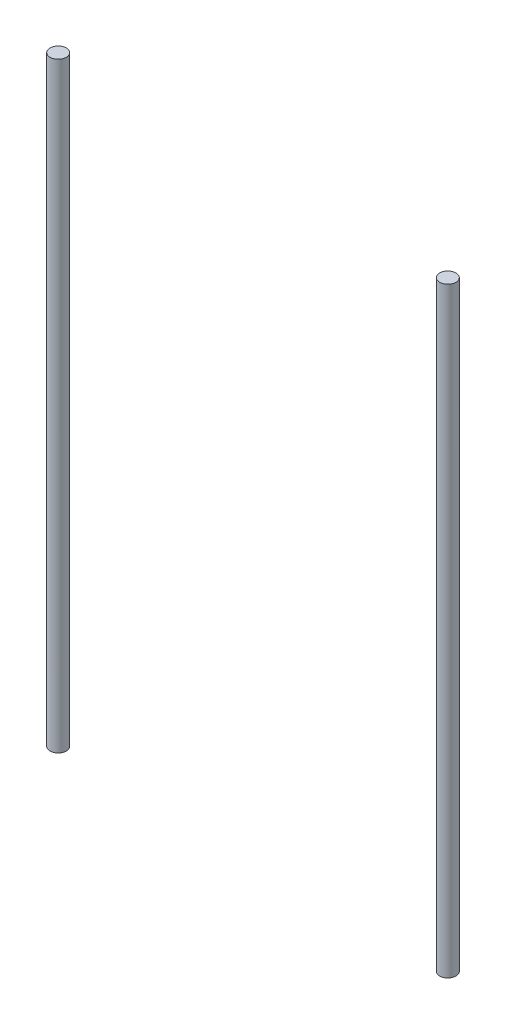
SolidWorks part; units mm, degrees
ref_plane "Front Plane" through (0, 0, 0) normal (0, 0, 1) x (1, 0, 0)
ref_plane "Top Plane" through (0, 0, 0) normal (0, 1, 0) x (1, 0, 0)
ref_plane "Right Plane" through (0, 0, 0) normal (1, 0, 0) x (0, 0, -1)
sketch "Sketch1" plane through (0, 0, 0) normal (0, 0, 1) x (1, 0, 0)
  line L0 (0, 0) -> (0, 245) construction
  line L1 (-287.5, 470) -> (287.5, 470)
  line L2 (-287.5, 470) -> (-287.5, -470)
  line L3 (-287.5, -470) -> (287.5, -470)
  line L4 (287.5, 470) -> (287.5, -470)
  line L5 (-287.5, 470) -> (287.5, -470) construction
  line L6 (-287.5, -470) -> (287.5, 470) construction
  line L7 (240, 60) -> (-240, 60)
  line L8 (240, 60) -> (240, 430)
  line L9 (240, 430) -> (-240, 430)
  line L10 (-240, 60) -> (-240, 430)
  line L11 (240, 60) -> (-240, 430) construction
  line L12 (240, 430) -> (-240, 60) construction
  point P0 (0, 0)
  point P6 (0, 245)
  dimension "D1" = 575
  dimension "D2" = 940
  dimension "D3" = 530
  dimension "D4" = 370
  dimension "D5" = 480
extrude "Boss-Extrude1" add sketch "Sketch1" along normal blind 12
sketch "Sketch2" plane through (0, 0, 0) normal (0, 1, 0) x (1, 0, 0)
  line L0 (287.5, 0) -> (317.5, 0) construction
  line L1 (304.8, -12.7) -> (317.5, -12.7) construction
  line L2 (317.5, 0) -> (317.5, -12.7) construction
  circle A0 centre (304.8, -12.7) radius 12.7
  dimension "D1" = 25.4
  dimension "D2" = 30
extrude "Boss-Extrude2" add sketch "Sketch2" along normal up to surface and the other way up to surface separate body up to face at (0, 470, 6) other way up to face at (0, -470, 6)
sketch "Sketch3" plane through (0, 0, 0) normal (0, 0, 1) x (1, 0, 0)
  line L0 (-287.5, 470) -> (-287.5, -470) construction
  line L1 (287.5, 470) -> (-287.5, 470)
  line L2 (287.5, 470) -> (287.5, -470)
  line L3 (287.5, -470) -> (-287.5, -470)
  line L4 (-287.5, 470) -> (-287.5, -470)
extrude "Cut-Extrude2" cut sketch "Sketch3" along normal through all
mirror "Mirror2" about plane through (0, 0, 0) normal (1, 0, 0) of bodies 102
